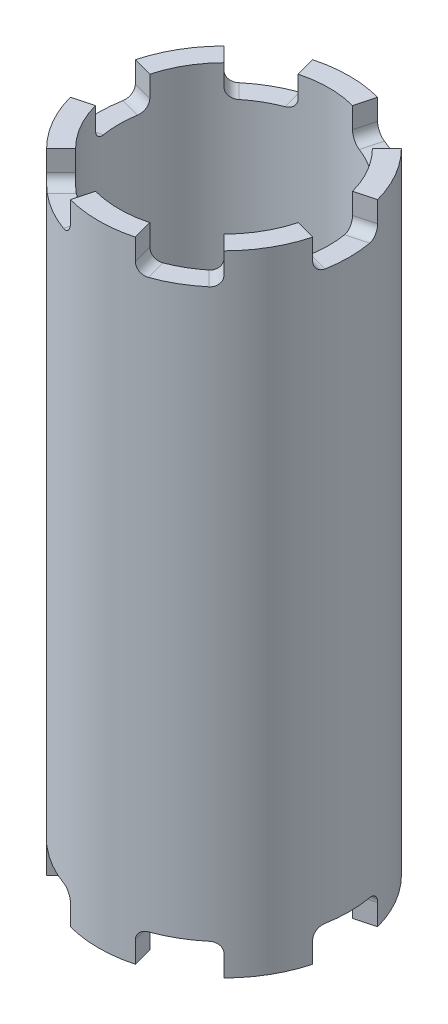
SolidWorks part; units mm, degrees
ref_plane "Front Plane" through (0, 0, 0) normal (0, 0, 1) x (1, 0, 0)
ref_plane "Top Plane" through (0, 0, 0) normal (0, 1, 0) x (1, 0, 0)
ref_plane "Right Plane" through (0, 0, 0) normal (1, 0, 0) x (0, 0, -1)
sketch "Sketch1" plane through (0, 0, 0) normal (0, 1, 0) x (1, 0, 0)
  circle A0 centre (0, 0) radius 30.353
  circle A1 centre (0, 0) radius 25.4
  dimension "D1" = 60.706
  dimension "D2" = 50.8
extrude "Boss-Extrude1" add sketch "Sketch1" along normal blind 152.4
sketch "Sketch2" plane through (0, 152.4, 0) normal (0, 1, 0) x (1, 0, 0)
  line L0 (24.5345, 6.574) -> (29.3187, 7.8559)
  line L1 (39.8175, -31.3258) -> (18.82, 47.0377) construction
  line L2 (20.2336, 22.6254) -> (28.8355, -9.4774) construction
  line L3 (0, 0) -> (73.2248, 0) construction
  line L4 (24.5345, -6.574) -> (29.3187, -7.8559)
  line L5 (6.574, -24.5345) -> (7.8559, -29.3187)
  line L6 (17.9605, -17.9605) -> (21.4628, -21.4628)
  line L7 (-17.9605, -17.9605) -> (-21.4628, -21.4628)
  line L8 (-6.574, -24.5345) -> (-7.8559, -29.3187)
  line L9 (-24.5345, 6.574) -> (-29.3187, 7.8559)
  line L10 (-24.5345, -6.574) -> (-29.3187, -7.8559)
  line L11 (-6.574, 24.5345) -> (-7.8559, 29.3187)
  line L12 (-17.9605, 17.9605) -> (-21.4628, 21.4628)
  line L13 (17.9605, 17.9605) -> (21.4628, 21.4628)
  line L14 (6.574, 24.5345) -> (7.8559, 29.3187)
  line L15 (0, 0) -> (24.5345, -6.574) construction
  line L16 (0, 0) -> (6.574, -24.5345) construction
  circle A0 centre (0, 0) radius 25.4 construction
  circle A1 centre (0, 0) radius 30.353 construction
  arc A2 (29.3187, 7.8559) -> (29.3187, -7.8559) centre (0, 0) cw
  arc A3 (24.5345, 6.574) -> (24.5345, -6.574) centre (0, 0) cw
  arc A4 (21.4628, -21.4628) -> (7.8559, -29.3187) centre (0, 0) cw
  arc A5 (17.9605, -17.9605) -> (6.574, -24.5345) centre (0, 0) cw
  arc A6 (-7.8559, -29.3187) -> (-21.4628, -21.4628) centre (0, 0) cw
  arc A7 (-6.574, -24.5345) -> (-17.9605, -17.9605) centre (0, 0) cw
  arc A8 (-29.3187, -7.8559) -> (-29.3187, 7.8559) centre (0, 0) cw
  arc A9 (-24.5345, -6.574) -> (-24.5345, 6.574) centre (0, 0) cw
  arc A10 (-21.4628, 21.4628) -> (-7.8559, 29.3187) centre (0, 0) cw
  arc A11 (-17.9605, 17.9605) -> (-6.574, 24.5345) centre (0, 0) cw
  arc A12 (7.8559, 29.3187) -> (21.4628, 21.4628) centre (0, 0) cw
  arc A13 (6.574, 24.5345) -> (17.9605, 17.9605) centre (0, 0) cw
  point P8 (29.3187, 7.8559)
  point P10 (29.3187, 7.8559)
  point P12 (24.5345, 6.574)
  point P14 (24.5345, 6.574)
  dimension "D2" = 6
  dimension "D1" = 60
  dimension "D3" = 30
extrude "Cut-Extrude2" cut sketch "Sketch2" against normal blind 7.62
fillet "Fillet1" radius 2.54 12 edges at (26.9266, 144.78, 7.215) (19.7117, 144.78, 19.7117) (-7.215, 144.78, 26.9266) (7.215, 144.78, 26.9266) (26.9266, 144.78, -7.215) (19.7117, 144.78, -19.7117) (7.215, 144.78, -26.9266) (-26.9266, 144.78, 7.215) (-26.9266, 144.78, -7.215) (-19.7117, 144.78, -19.7117) (-7.215, 144.78, -26.9266) (-19.7117, 144.78, 19.7117)
ref_plane "Plane4" through (0, 76.2, 0) normal (0, -1, 0) x (-1, 0, 0)
mirror "Mirror1" about plane through (0, 76.2, 0) normal (0, -1, 0) of "Fillet1", "Cut-Extrude2"
